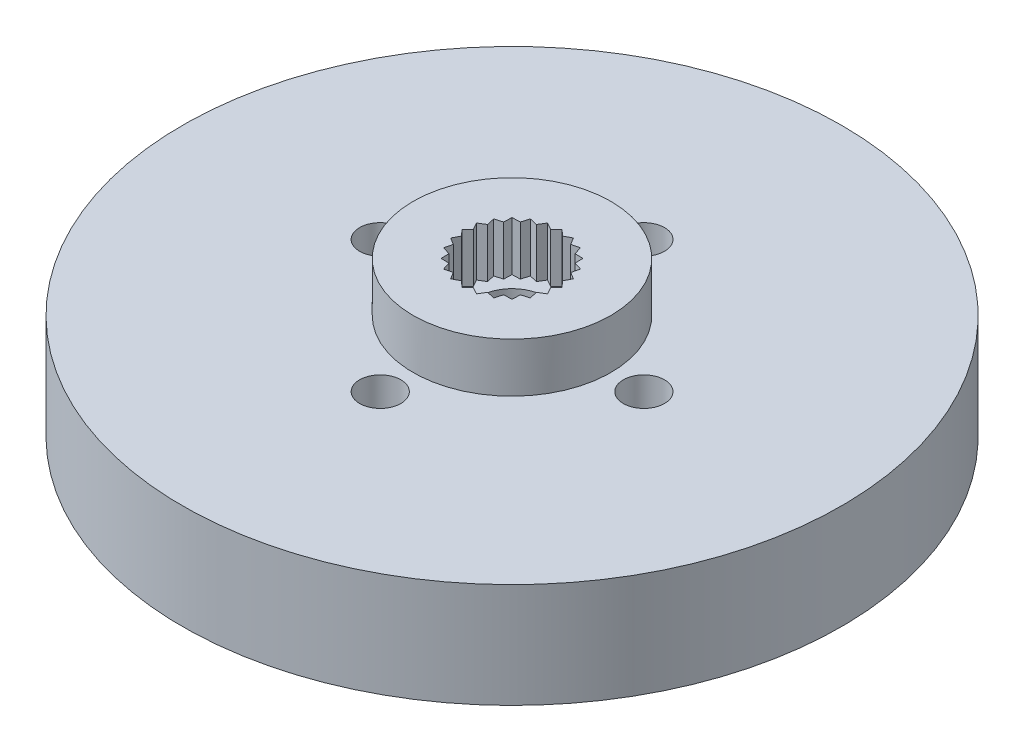
SolidWorks part; units mm, degrees
ref_plane "Front" through (0, 0, 0) normal (0, 0, 1) x (1, 0, 0)
ref_plane "Top" through (0, 0, 0) normal (0, 1, 0) x (1, 0, 0)
ref_plane "Right" through (0, 0, 0) normal (1, 0, 0) x (0, 0, -1)
sketch "Sketch1" plane through (0, 0, 0) normal (0, 1, 0) x (1, 0, 0)
  line L0 (-0.0041, 3.0416) -> (-0.3602, 2.7054)
  line L1 (-0.0041, 3.0416) -> (0.352, 2.7054)
  line L2 (-0.0041, 0.0007) -> (-0.0041, 1.632) construction
  line L3 (0.783, 2.938) -> (1.0399, 2.5211)
  line L4 (0.783, 2.938) -> (0.352, 2.7054)
  line L5 (1.5164, 2.6342) -> (1.6566, 2.165)
  line L6 (1.5164, 2.6342) -> (1.0399, 2.5211)
  line L7 (2.1462, 2.151) -> (2.1602, 1.6614)
  line L8 (2.1462, 2.151) -> (1.6566, 2.165)
  line L9 (2.6294, 1.5212) -> (2.5163, 1.0447)
  line L10 (2.6294, 1.5212) -> (2.1602, 1.6614)
  line L11 (2.9332, 0.7877) -> (2.7006, 0.3568)
  line L12 (2.9332, 0.7877) -> (2.5163, 1.0447)
  line L13 (3.0369, 0.0007) -> (2.7006, -0.3554)
  line L14 (3.0369, 0.0007) -> (2.7006, 0.3568)
  line L15 (2.9332, -0.7864) -> (2.5163, -1.0433)
  line L16 (2.9332, -0.7864) -> (2.7006, -0.3554)
  line L17 (2.6294, -1.5198) -> (2.1602, -1.66)
  line L18 (2.6294, -1.5198) -> (2.5163, -1.0433)
  line L19 (2.1462, -2.1496) -> (1.6566, -2.1636)
  line L20 (2.1462, -2.1496) -> (2.1602, -1.66)
  line L21 (1.5164, -2.6329) -> (1.0399, -2.5197)
  line L22 (1.5164, -2.6329) -> (1.6566, -2.1636)
  line L23 (0.783, -2.9367) -> (0.352, -2.704)
  line L24 (0.783, -2.9367) -> (1.0399, -2.5197)
  line L25 (-0.0041, -3.0403) -> (-0.3602, -2.704)
  line L26 (-0.0041, -3.0403) -> (0.352, -2.704)
  line L27 (-0.7912, -2.9367) -> (-1.0481, -2.5197)
  line L28 (-0.7912, -2.9367) -> (-0.3602, -2.704)
  line L29 (-1.5246, -2.6329) -> (-1.6648, -2.1636)
  line L30 (-1.5246, -2.6329) -> (-1.0481, -2.5197)
  line L31 (-2.1544, -2.1496) -> (-2.1684, -1.66)
  line L32 (-2.1544, -2.1496) -> (-1.6648, -2.1636)
  line L33 (-2.6376, -1.5198) -> (-2.5245, -1.0433)
  line L34 (-2.6376, -1.5198) -> (-2.1684, -1.66)
  line L35 (-2.9414, -0.7864) -> (-2.7088, -0.3554)
  line L36 (-2.9414, -0.7864) -> (-2.5245, -1.0433)
  line L37 (-3.045, 0.0007) -> (-2.7088, 0.3568)
  line L38 (-3.045, 0.0007) -> (-2.7088, -0.3554)
  line L39 (-2.9414, 0.7877) -> (-2.5245, 1.0447)
  line L40 (-2.9414, 0.7877) -> (-2.7088, 0.3568)
  line L41 (-2.6376, 1.5212) -> (-2.1684, 1.6614)
  line L42 (-2.6376, 1.5212) -> (-2.5245, 1.0447)
  line L43 (-2.1544, 2.151) -> (-1.6648, 2.165)
  line L44 (-2.1544, 2.151) -> (-2.1684, 1.6614)
  line L45 (-1.5246, 2.6342) -> (-1.0481, 2.5211)
  line L46 (-1.5246, 2.6342) -> (-1.6648, 2.165)
  line L47 (-0.7912, 2.938) -> (-0.3602, 2.7054)
  line L48 (-0.7912, 2.938) -> (-1.0481, 2.5211)
  circle A0 centre (-0.0041, 0.0007) radius 6
  point P49 (-0.0041, 0.0007)
  dimension "D2" = 12
  dimension "D1" = 93.28
extrude "Boss-Extrude1" add sketch "Sketch1" along normal blind 3
sketch "Sketch2" plane through (0, 0, 0) normal (0, -1, 0) x (1, 0, 0)
  circle A0 centre (0, 0) radius 20
  circle A1 centre (0, 0) radius 2
  circle A2 centre (8, 0) radius 1.25
  circle A10 centre (0, -8) radius 1.25
  circle A11 centre (-8, 0) radius 1.25
  circle A12 centre (0, 8) radius 1.25
  point P21 (0, 0)
  point P30 (0, 0)
  dimension "D1" = 40
  dimension "D2" = 4
  dimension "D3" = 2.5
  dimension "D4" = 8
  dimension "D5" = 4
extrude "Boss-Extrude2" add sketch "Sketch2" along normal blind 6.35
